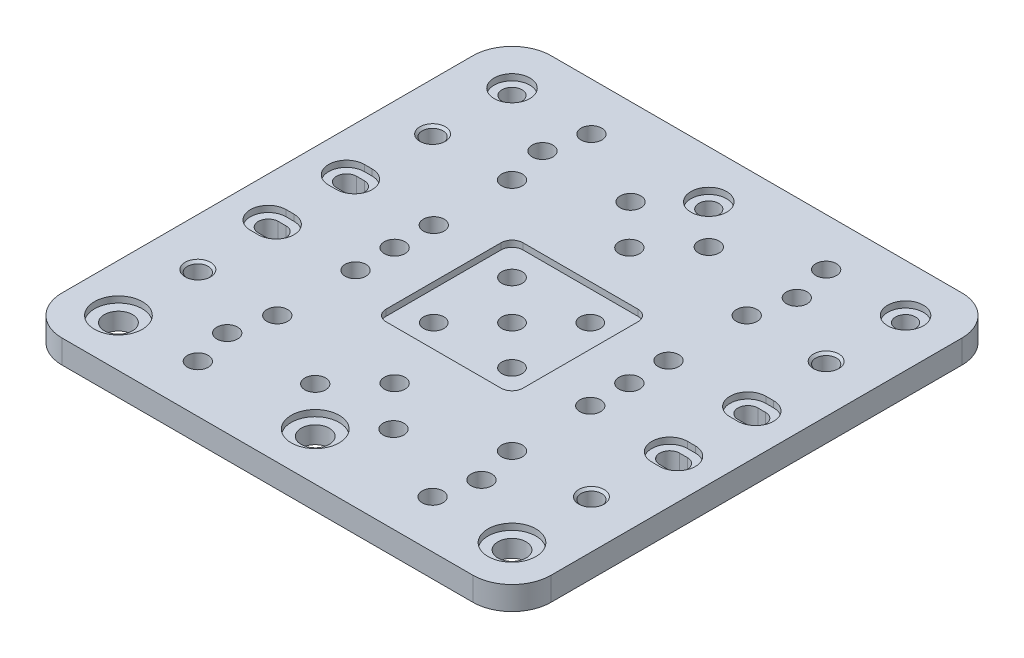
SolidWorks part; units mm, degrees
material "6061-T6 (SS)"
ref_plane "Front Plane" through (0, 0, 0) normal (0, 0, 1) x (1, 0, 0)
ref_plane "Top Plane" through (0, 0, 0) normal (0, 1, 0) x (1, 0, 0)
ref_plane "Right Plane" through (0, 0, 0) normal (1, 0, 0) x (0, 0, -1)
sketch "Sketch1" plane through (0, 0, 0) normal (0, 1, 0) x (1, 0, 0)
  line L1 (-62.5, 62.5) -> (62.5, 62.5)
  line L2 (-62.5, 62.5) -> (-62.5, -62.5)
  line L3 (-62.5, -62.5) -> (62.5, -62.5)
  line L4 (62.5, 62.5) -> (62.5, -62.5)
  line L5 (-62.5, 62.5) -> (62.5, -62.5) construction
  line L6 (-62.5, -62.5) -> (62.5, 62.5) construction
  point P0 (0, 0)
  dimension "D1" = 125
  dimension "D2" = 125
extrude "Boss-Extrude1" add sketch "Sketch1" along normal blind 6
sketch "Sketch2" plane through (0, 6, 0) normal (0, 1, 0) x (1, 0, 0)
  line L0 (-62.5, -50.3) -> (62.5, -50.3) construction
  line L1 (-62.5, 62.5) -> (-62.5, -62.5) construction
  line L2 (62.5, -62.5) -> (62.5, 62.5) construction
  line L3 (-62.5, -62.5) -> (62.5, -62.5) construction
  line L4 (-50.3, -50.3) -> (-50.3, -62.5) construction
  line L6 (0, -50.3) -> (0, -62.5) construction
  line L7 (50.3, -62.5) -> (50.3, -50.3) construction
  line L8 (-3.3, 0) -> (3.3, 0) construction
  line L9 (50.3, 62.5) -> (50.3, 50.3) construction
  line L10 (0, 50.3) -> (0, 62.5) construction
  line L11 (-50.3, 50.3) -> (-50.3, 62.5) construction
  line L12 (-62.5, 50.3) -> (62.5, 50.3) construction
  line L13 (-50.3, -50.3) -> (-50.3, 29.9) construction
  line L14 (-62.5, 29.9) -> (-50.3, 29.9) construction
  line L15 (62.5, 62.5) -> (-62.5, 62.5) construction
  dimension "D1" = 12.2
  dimension "D2" = 12.2
  dimension "D3" = 12.2
  dimension "D4" = 32.6
hole_wizard "CBORE for M6.5 SHSS1" positions "Sketch3" profile "Sketch4" counterbore size "M6.5" standard "ANSI Metric" end condition through all
sketch "Sketch3" plane through (0, 6, 0) normal (0, 1, 0) x (1, 0, 0)
  point P0 (-50.3, -50.3)
  point P3 (0, -50.3)
  point P6 (50.3, -50.3)
sketch "Sketch4" plane through (-50.3, 6, 50.3) normal (1, 0, 0) x (0, 0, 1)
  line L0 (0, 0) -> (0, 6)
  line L1 (0, 6) -> (3.6, 6)
  line L3 (3.6, 6) -> (3.6, 1.6)
  line L4 (3.6, 1.6) -> (6.125, 1.6)
  line L5 (6.125, 1.6) -> (6.125, 0)
  line L7 (6.125, 0) -> (0, 0)
  line L11 (0, -6.35) -> (0, 107.95) construction
  dimension "Thru Hole Dia." = 7.2
  dimension "Thru Hole Depth" = 6
  dimension "C'Bore Dia." = 12.25
  dimension "C'Bore Depth" = 1.6
hole_wizard "Hole1" positions "Sketch6" profile "Sketch7" legacy
sketch "Sketch6" plane through (0, 6, 0) normal (0, 1, 0) x (1, 0, 0)
  point P0 (-50.3, 50.3)
  point P3 (0, 50.3)
  point P6 (50.3, 50.3)
sketch "Sketch7" plane through (-50.3, 6, -50.3) normal (1, 0, 0) x (0, 0, 1)
  line L0 (0, 0) -> (0, 7.5322)
  line L1 (0, 7.5322) -> (2.55, 6)
  line L2 (2.55, 6) -> (2.55, 1.6)
  line L3 (2.55, 1.6) -> (4.57, 1.6)
  line L4 (4.57, 0) -> (0, 0)
  line L5 (0, -11.3109) -> (0, 121.1557) construction
  line L6 (0, 7.5322) -> (-2.55, 6) construction
  line L7 (4.57, 1.6) -> (4.57, 0)
  dimension "Depth" = 6
  dimension "Drill Angle" = 118
  dimension "Diameter" = 5.1
  dimension "C-Bore Diameter" = 9.14
  dimension "C-Bore Depth" = 1.6
sketch "Sketch10" plane through (0, 6, 0) normal (0, 1, 0) x (1, 0, 0)
  line L0 (-32.5, 62.5) -> (-32.5, 40.3) construction
  line L1 (62.5, 62.5) -> (-62.5, 62.5) construction
  line L2 (-62.5, -62.5) -> (62.5, -62.5) construction
  line L3 (-62.5, 62.5) -> (-62.5, -62.5) construction
  line L4 (-30, 62.5) -> (-30, 50.3) construction
  line L5 (-62.5, 50.3) -> (-30, 50.3) construction
  line L6 (62.5, -62.5) -> (62.5, 62.5) construction
  line L7 (-62.5, 40.3) -> (-32.5, 40.3) construction
  line L8 (-62.5, 30) -> (-30, 30) construction
  line L9 (-30, 10) -> (62.5, 10) construction
  line L10 (-30, 0) -> (62.5, 0) construction
  line L11 (-30, 30) -> (-30, -30) construction
  line L12 (0, 62.5) -> (0, 50.3) construction
  line L13 (32.5, 40.3) -> (10, 40.3) construction
  line L14 (-32.5, 40.3) -> (-10, 40.3) construction
  line L15 (0, 30) -> (0, -62.5) construction
  line L16 (30, 30) -> (30, -30) construction
  line L17 (0, 50.3) -> (62.5, 50.3) construction
  line L18 (0, 30) -> (62.5, 30) construction
  line L19 (30, 0) -> (-62.5, 0) construction
  line L20 (30, 10) -> (-62.5, 10) construction
  line L21 (62.5, 30) -> (30, 30) construction
  line L22 (62.5, 40.3) -> (32.5, 40.3) construction
  line L23 (62.5, 50.3) -> (30, 50.3) construction
  line L24 (30, 62.5) -> (30, 50.3) construction
  line L25 (32.5, 62.5) -> (32.5, 40.3) construction
  line L26 (32.5, -62.5) -> (32.5, -40.3) construction
  line L27 (30, -62.5) -> (30, -50.3) construction
  line L28 (62.5, -50.3) -> (30, -50.3) construction
  line L29 (62.5, -40.3) -> (32.5, -40.3) construction
  line L30 (62.5, -30) -> (30, -30) construction
  line L31 (30, -10) -> (-62.5, -10) construction
  line L32 (0, -30) -> (62.5, -30) construction
  line L33 (0, -50.3) -> (62.5, -50.3) construction
  line L34 (0, -30) -> (0, 62.5) construction
  line L35 (-32.5, -40.3) -> (-10, -40.3) construction
  line L36 (32.5, -40.3) -> (10, -40.3) construction
  line L37 (0, -62.5) -> (0, -50.3) construction
  line L38 (-30, -10) -> (62.5, -10) construction
  line L39 (-62.5, -30) -> (-30, -30) construction
  line L40 (-62.5, -40.3) -> (-32.5, -40.3) construction
  line L41 (-62.5, -50.3) -> (-30, -50.3) construction
  line L42 (-30, -62.5) -> (-30, -50.3) construction
  line L43 (-32.5, -62.5) -> (-32.5, -40.3) construction
  line L44 (-50.3, 62.5) -> (-50.3, 30) construction
  line L45 (50.3, 62.5) -> (50.3, 30) construction
  line L46 (62.5, 30) -> (30, 30) construction
  line L47 (-50.3, -62.5) -> (-50.3, -30) construction
  line L48 (-62.5, -30) -> (-30, -30) construction
  line L49 (62.5, -30) -> (30, -30) construction
  line L50 (50.3, -62.5) -> (50.3, -30) construction
  line L51 (62.5, -30) -> (30, -30) construction
  line L52 (0, -30) -> (62.5, -30) construction
  dimension "D1" = 30
  dimension "D2" = 32.5
  dimension "D3" = 12.2
  dimension "D4" = 22.2
  dimension "D5" = 32.5
  dimension "D6" = 52.5
  dimension "D7" = 12.2
  dimension "D8" = 52.5
hole_wizard "Ø5.3 (5.3) Diameter Hole1" positions "Sketch11" profile "Sketch12" hole size "Ø5.3" standard "ANSI Metric" end condition through all
sketch "Sketch11" plane through (0, 6, 0) normal (0, 1, 0) x (1, 0, 0)
  point P0 (-30, 50.3)
  point P3 (-32.5, 40.3)
  point P6 (-30, 30)
  point P9 (-10, 40.3)
  point P12 (0, 30)
  point P15 (-30, 10)
  point P18 (-30, 0)
sketch "Sketch12" plane through (-30, 6, -50.3) normal (1, 0, 0) x (0, 0, 1)
  line L0 (0, 0) -> (0, 6)
  line L1 (0, 6) -> (2.65, 6)
  line L2 (2.65, 6) -> (2.65, 0)
  line L5 (2.65, 0) -> (0, 0)
  line L11 (0, -6.35) -> (0, 107.95) construction
  dimension "Thru Hole Dia." = 5.3
  dimension "Thru Hole Depth" = 6
hole_wizard "Ø5.3 (5.3) Diameter Hole2" positions "Sketch23" profile "Sketch24" hole size "Ø5.3" standard "ANSI Metric" end condition through all
sketch "Sketch23" plane through (0, 6, 0) normal (0, 1, 0) x (1, 0, 0)
  point P0 (10, 40.3)
  point P3 (30, 50.3)
  point P6 (32.5, 40.3)
  point P9 (30, 30)
  point P12 (30, 10)
  point P15 (30, 0)
  point P18 (30, -10)
  point P21 (-30, -10)
  point P24 (-30, -30)
  point P27 (0, -30)
  point P30 (30, -30)
  point P33 (10, -40.3)
  point P36 (-10, -40.3)
  point P39 (-32.5, -40.3)
  point P42 (32.5, -40.3)
  point P45 (30, -50.3)
  point P48 (-30, -50.3)
sketch "Sketch24" plane through (10, 6, -40.3) normal (1, 0, 0) x (0, 0, 1)
  line L0 (0, 0) -> (0, 6)
  line L1 (0, 6) -> (2.65, 6)
  line L2 (2.65, 6) -> (2.65, 0)
  line L5 (2.65, 0) -> (0, 0)
  line L11 (0, -6.35) -> (0, 107.95) construction
  dimension "Thru Hole Dia." = 5.3
  dimension "Thru Hole Depth" = 6
sketch "Sketch13" plane through (0, 6, 0) normal (0, 1, 0) x (1, 0, 0)
  line L0 (52.3, 10) -> (62.5, 10) construction
  line L1 (51.3, 10) -> (-62.5, 10) construction
  line L2 (62.5, -62.5) -> (62.5, 62.5) construction
  line L3 (52.3, 62.5) -> (52.3, 10) construction
  line L4 (62.5, 62.5) -> (-62.5, 62.5) construction
  line L6 (52.3, 10) -> (50.3, 10) construction
  line L7 (-30, 10) -> (62.5, 10) construction
  line L8 (52.3, 5.43) -> (50.3, 5.43)
  line L9 (52.3, 14.57) -> (50.3, 14.57)
  line L11 (-52.3, 62.5) -> (-52.3, -62.5) construction
  line L12 (-62.5, -62.5) -> (62.5, -62.5) construction
  line L13 (-62.5, 62.5) -> (-62.5, -62.5) construction
  line L14 (-62.5, -10) -> (62.5, -10) construction
  line L15 (52.3, -62.5) -> (52.3, 62.5) construction
  line L16 (-52.3, 10) -> (-50.3, 10) construction
  line L17 (-52.3, 14.57) -> (-50.3, 14.57)
  line L18 (-52.3, 5.43) -> (-50.3, 5.43)
  line L19 (-52.3, -10) -> (-50.3, -10) construction
  line L20 (-52.3, -5.43) -> (-50.3, -5.43)
  line L21 (-52.3, -14.57) -> (-50.3, -14.57)
  line L22 (52.3, -10) -> (50.3, -10) construction
  line L23 (52.3, -14.57) -> (50.3, -14.57)
  line L24 (52.3, -5.43) -> (50.3, -5.43)
  arc A0 (52.3, 5.43) -> (52.3, 14.57) centre (52.3, 10) ccw
  arc A1 (50.3, 14.57) -> (50.3, 5.43) centre (50.3, 10) ccw
  arc A2 (-52.3, 14.57) -> (-52.3, 5.43) centre (-52.3, 10) ccw
  arc A3 (-50.3, 5.43) -> (-50.3, 14.57) centre (-50.3, 10) ccw
  arc A4 (-52.3, -5.43) -> (-52.3, -14.57) centre (-52.3, -10) ccw
  arc A5 (-50.3, -14.57) -> (-50.3, -5.43) centre (-50.3, -10) ccw
  arc A6 (52.3, -14.57) -> (52.3, -5.43) centre (52.3, -10) ccw
  arc A7 (50.3, -5.43) -> (50.3, -14.57) centre (50.3, -10) ccw
  point P0 (51.3, 10)
  point P27 (-52.3, 10)
  point P28 (-52.3, -10)
  point P29 (52.3, -10)
  point P32 (-51.3, 10)
  point P37 (-51.3, -10)
  point P44 (51.3, -10)
  dimension "D4" = 4.57
  dimension "D1" = 10.2
  dimension "D2" = 52.5
  dimension "D3" = 2
  dimension "D5" = 10.2
  dimension "D6" = 52.5
  dimension "D7" = 10.2
extrude "Cut-Extrude1" cut sketch "Sketch13" against normal blind 1.6
sketch "Sketch15" plane through (0, 4.4, 0) normal (0, 1, 0) x (1, 0, 0)
  line L0 (52.3, 10) -> (50.3, 10) construction
  line L1 (-30, 10) -> (62.5, 10) construction
  line L2 (52.3, 7.45) -> (50.3, 7.45)
  line L3 (52.3, 12.55) -> (50.3, 12.55)
  line L4 (62.5, -62.5) -> (62.5, 62.5) construction
  line L5 (-52.3, 10) -> (-50.3, 10) construction
  line L6 (-52.3, 12.55) -> (-50.3, 12.55)
  line L7 (-52.3, 7.45) -> (-50.3, 7.45)
  line L8 (-52.3, -10) -> (-50.3, -10) construction
  line L9 (-52.3, -7.45) -> (-50.3, -7.45)
  line L10 (-52.3, -12.55) -> (-50.3, -12.55)
  line L11 (50.3, -10) -> (52.3, -10) construction
  line L12 (50.3, -7.45) -> (52.3, -7.45)
  line L13 (50.3, -12.55) -> (52.3, -12.55)
  line L14 (-62.5, 62.5) -> (-62.5, -62.5) construction
  arc A0 (52.3, 7.45) -> (52.3, 12.55) centre (52.3, 10) ccw
  arc A1 (50.3, 12.55) -> (50.3, 7.45) centre (50.3, 10) ccw
  arc A2 (-52.3, 12.55) -> (-52.3, 7.45) centre (-52.3, 10) ccw
  arc A3 (-50.3, 7.45) -> (-50.3, 12.55) centre (-50.3, 10) ccw
  arc A4 (-52.3, -7.45) -> (-52.3, -12.55) centre (-52.3, -10) ccw
  arc A5 (-50.3, -12.55) -> (-50.3, -7.45) centre (-50.3, -10) ccw
  arc A6 (50.3, -7.45) -> (50.3, -12.55) centre (50.3, -10) ccw
  arc A7 (52.3, -12.55) -> (52.3, -7.45) centre (52.3, -10) ccw
  point P4 (51.3, 10)
  point P13 (-51.3, 10)
  point P18 (-51.3, -10)
  point P26 (51.3, -10)
  dimension "D3" = 2.55
  dimension "D1" = 10.2
  dimension "D2" = 2
  dimension "D4" = 10.2
  dimension "D5" = 10.2
extrude "Cut-Extrude2" cut sketch "Sketch15" against normal through all
sketch "Sketch16" plane through (0, 6, 0) normal (0, 1, 0) x (1, 0, 0)
  line L1 (-17.5, 17.5) -> (17.5, 17.5)
  line L2 (-17.5, 17.5) -> (-17.5, -17.5)
  line L3 (-17.5, -17.5) -> (17.5, -17.5)
  line L4 (17.5, 17.5) -> (17.5, -17.5)
  line L5 (-17.5, 17.5) -> (17.5, -17.5) construction
  line L6 (-17.5, -17.5) -> (17.5, 17.5) construction
  point P0 (0, 0)
  dimension "D1" = 35
  dimension "D2" = 35
extrude "Cut-Extrude3" cut sketch "Sketch16" against normal blind 1.6
sketch "Sketch17" plane through (0, 4.4, 0) normal (0, 1, 0) x (1, 0, 0)
  line L0 (10, 17.5) -> (10, 10) construction
  line L1 (17.5, 17.5) -> (-17.5, 17.5) construction
  line L2 (17.5, -10) -> (10, -10) construction
  line L3 (-10, -17.5) -> (-10, -10) construction
  line L4 (-17.5, 10) -> (-10, 10) construction
  point P13 (0, 0)
  dimension "D1" = 10
  dimension "D2" = 10
  dimension "D3" = 4
hole_wizard "Ø5.2 (5.2) Diameter Hole1" positions "Sketch21" profile "Sketch22" hole size "Ø5.2" standard "ANSI Metric" end condition through all
sketch "Sketch21" plane through (0, 4.4, 0) normal (0, 1, 0) x (1, 0, 0)
  point P0 (-10, 10)
  point P3 (0, 0)
  point P6 (10, 10)
  point P9 (10, -10)
  point P12 (-10, -10)
sketch "Sketch22" plane through (-10, 4.4, -10) normal (1, 0, 0) x (0, 0, 1)
  line L0 (0, 0) -> (0, 4.4)
  line L1 (0, 4.4) -> (2.6, 4.4)
  line L2 (2.6, 4.4) -> (2.6, 0)
  line L5 (2.6, 0) -> (0, 0)
  line L11 (0, -6.35) -> (0, 107.95) construction
  dimension "Thru Hole Dia." = 5.2
  dimension "Thru Hole Depth" = 4.4
fillet "Fillet1" radius 10 4 edges at (-62.5, 3, 62.5) (-62.5, 3, -62.5) (62.5, 3, -62.5) (62.5, 3, 62.5)
fillet "Fillet2" radius 2.8 4 edges at (17.5, 5.2, 17.5) (-17.5, 5.2, 17.5) (17.5, 5.2, -17.5) (-17.5, 5.2, -17.5)
hole_wizard "Ø5.3 (5.3) Diameter Hole3" positions "Sketch25" profile "Sketch26" hole size "Ø5.3" standard "ANSI Metric" end condition through all
sketch "Sketch25" plane through (0, 6, 0) normal (0, 1, 0) x (1, 0, 0)
  point P0 (-50.3, 30)
  point P3 (50.3, 30)
  point P6 (50.3, -30)
  point P9 (-50.3, -30)
sketch "Sketch26" plane through (-50.3, 6, -30) normal (1, 0, 0) x (0, 0, 1)
  line L0 (0, 0) -> (0, 6)
  line L1 (0, 6) -> (2.65, 6)
  line L2 (2.65, 6) -> (2.65, 0)
  line L5 (2.65, 0) -> (0, 0)
  line L11 (0, -6.35) -> (0, 107.95) construction
  dimension "Thru Hole Dia." = 5.3
  dimension "Thru Hole Depth" = 6
chamfer "Chamfer1" distance 0.6 angle 45 4 edges at (-50.3, 6, 32.65) (50.3, 6, 32.65) (50.3, 6, -27.35) (-50.3, 6, -27.35)
